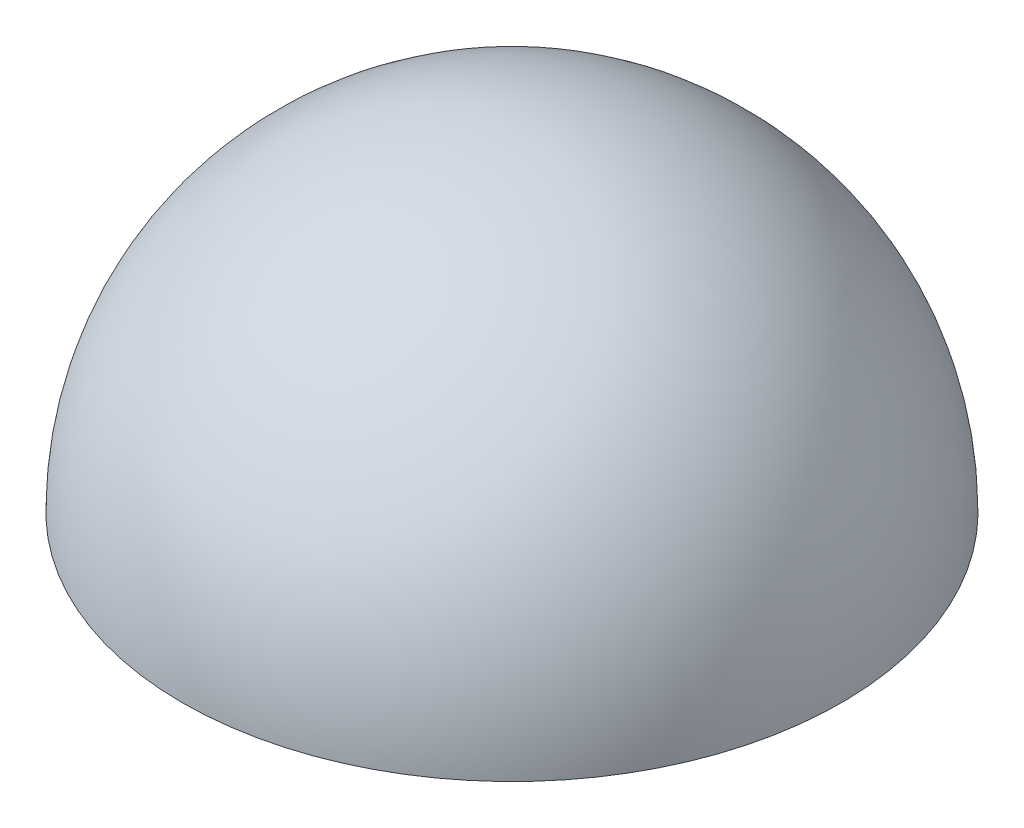
SolidWorks part; units mm, degrees
ref_plane "Front Plane" through (0, 0, 0) normal (0, 0, 1) x (1, 0, 0)
ref_plane "Top Plane" through (0, 0, 0) normal (0, 1, 0) x (1, 0, 0)
ref_plane "Right Plane" through (0, 0, 0) normal (1, 0, 0) x (0, 0, -1)
sketch "Sketch1" plane through (0, 0, 0) normal (0, 1, 0) x (1, 0, 0)
  line L0 (0, 9) -> (0, -9)
  arc A0 (0, 9) -> (0, -9) centre (0, 0) ccw
  dimension "D1" = 18
revolve "Revolve1" add sketch "Sketch1" angle 360 about L0
sketch "Sketch2" plane through (0, 0, 0) normal (0, 0, 1) x (1, 0, 0)
  line L0 (-9.4131, 0) -> (9.8177, 0)
  line L1 (9.8177, 0) -> (9.8177, -9.1988)
  line L2 (9.8177, -9.1988) -> (-9.4131, -9.1988)
  line L3 (-9.4131, -9.1988) -> (-9.4131, 0)
  dimension "D1" = 9.1988
  dimension "D2" = 9.4131
  dimension "D3" = 9.8177
extrude "Cut-Extrude1" cut sketch "Sketch2" against normal through all both and the other way through all
